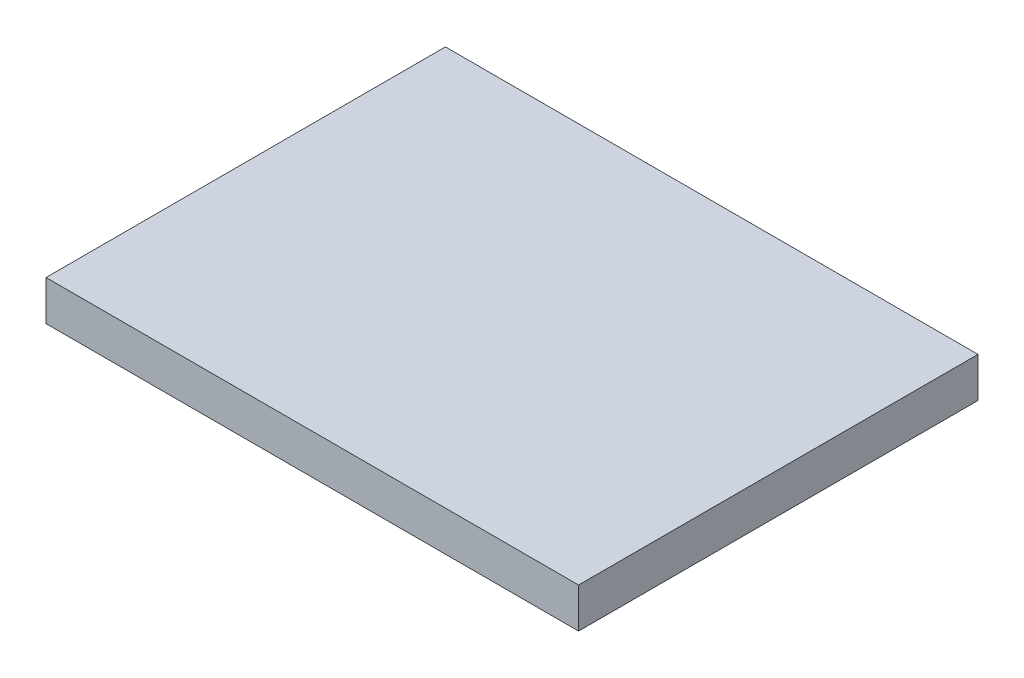
SolidWorks part; units mm, degrees
material "AISI 1020"
ref_plane "Front Plane" through (0, 0, 0) normal (0, 0, 1) x (1, 0, 0)
ref_plane "Top Plane" through (0, 0, 0) normal (0, 1, 0) x (1, 0, 0)
ref_plane "Right Plane" through (0, 0, 0) normal (1, 0, 0) x (0, 0, -1)
sketch "Sketch1" plane through (0, 0, 0) normal (0, 1, 0) x (1, 0, 0)
  line L1 (-20, 15) -> (20, 15)
  line L2 (-20, 15) -> (-20, -15)
  line L3 (-20, -15) -> (20, -15)
  line L4 (20, 15) -> (20, -15)
  line L5 (-20, 15) -> (20, -15) construction
  line L6 (-20, -15) -> (20, 15) construction
  point P0 (0, 0)
  dimension "D1" = 40
  dimension "D2" = 30
extrude "Boss-Extrude1" add sketch "Sketch1" along normal mid plane 3
